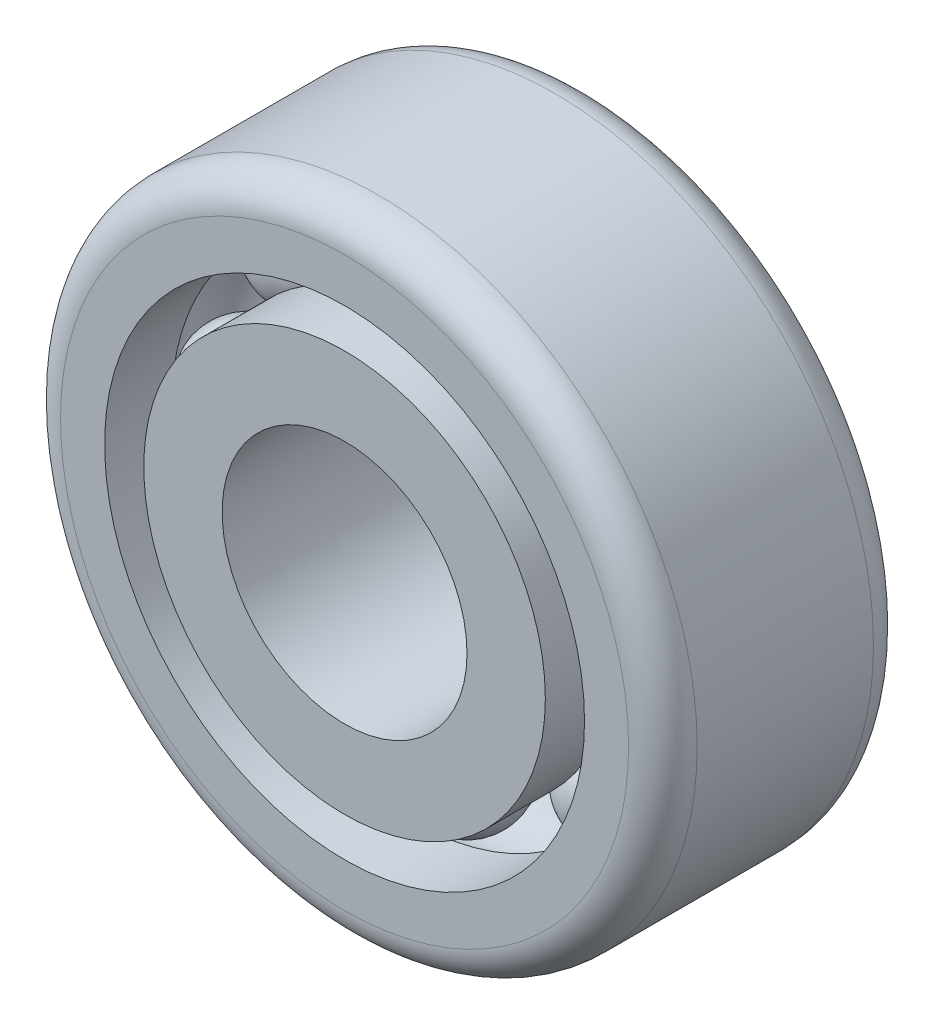
SolidWorks part; units mm, degrees
material "Alloy Steel"
ref_plane "Front Plane" through (0, 0, 0) normal (0, 0, 1) x (1, 0, 0)
ref_plane "Top Plane" through (0, 0, 0) normal (0, 1, 0) x (1, 0, 0)
ref_plane "Right Plane" through (0, 0, 0) normal (1, 0, 0) x (0, 0, -1)
sketch "Croquis5" plane through (0, 0, 0) normal (0, 1, 0) x (1, 0, 0)
  line L0 (0, 0) -> (0, 5.384) construction
sketch "Croquis3" plane through (0, 0, 0) normal (0, 1, 0) x (1, 0, 0)
  line L0 (-6.5, -2.5) -> (-2.5, 2.5) construction
  line L1 (-4.9, 2.5) -> (-6.5, 2.5)
  line L2 (-4.9, 2.5) -> (-4.9, 1.1314)
  line L3 (-4.9, -2.5) -> (-6.5, -2.5)
  line L4 (-6.5, 2.5) -> (-6.5, -2.5)
  line L5 (-4.9, 2.5) -> (-6.5, -2.5) construction
  line L6 (-4.9, -2.5) -> (-6.5, 2.5) construction
  line L7 (-4.1, 2.5) -> (-2.5, 2.5)
  line L8 (-4.1, 2.5) -> (-4.1, 1.1314)
  line L9 (-4.1, -2.5) -> (-2.5, -2.5)
  line L10 (-2.5, 2.5) -> (-2.5, -2.5)
  line L11 (-4.1, 2.5) -> (-2.5, -2.5) construction
  line L12 (-4.1, -2.5) -> (-2.5, 2.5) construction
  line L13 (-4.9, -1.1314) -> (-4.9, -2.5)
  line L14 (-4.1, -1.1314) -> (-4.1, -2.5)
  arc A0 (-4.9, 1.1314) -> (-4.9, -1.1314) centre (-4.5, 0) ccw
  arc A1 (-4.1, -1.1314) -> (-4.1, 1.1314) centre (-4.5, 0) ccw
  point P0 (-5.7, 0)
  point P5 (-3.3, 0)
  dimension "D1" = 2.5
  dimension "D2" = 6.5
  dimension "D3" = 1.6
  dimension "D4" = 5
revolve "Revolución4" add sketch "Croquis3" angle 360 about L0
sketch "Croquis4" plane through (0, 0, 0) normal (0, 1, 0) x (1, 0, 0)
  line L1 (-4.5, 1.0612) -> (-4.5, -1.0667)
  arc A1 (-4.5, -1.0667) -> (-4.5, 1.0612) centre (-4.5, -0.0028) ccw
revolve "Revolución3" add sketch "Croquis4" angle 360 about L1
pattern_circular "MatrizC4" count 8 over 360 about axis through (0, 0, 0) along (0, 0, 1) of bodies 139
fillet "Redondeo1" radius 0.7 2 edges at (6.5, 0, 2.5) (6.5, 0, -2.5)
